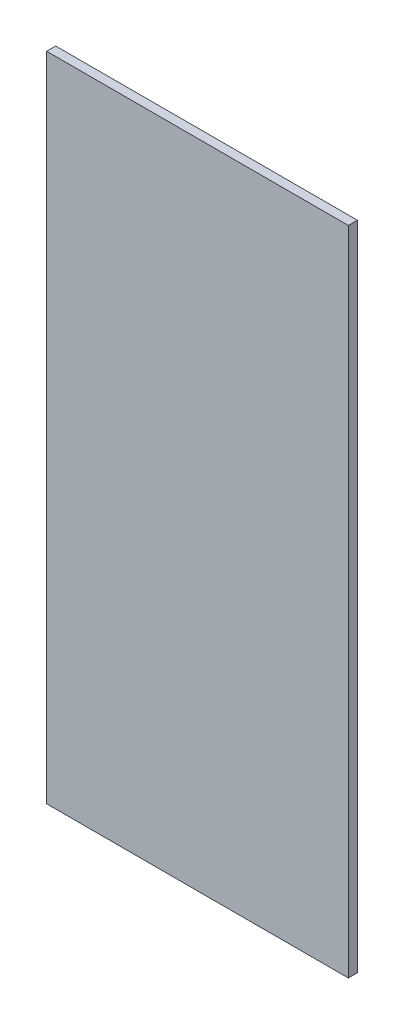
SolidWorks part; units mm, degrees
material "Pine"
ref_plane "Front Plane" through (0, 0, 0) normal (0, 0, 1) x (1, 0, 0)
ref_plane "Top Plane" through (0, 0, 0) normal (0, 1, 0) x (1, 0, 0)
ref_plane "Right Plane" through (0, 0, 0) normal (1, 0, 0) x (0, 0, -1)
sketch "Sketch1" plane through (0, 0, 0) normal (0, 0, 1) x (1, 0, 0)
  line L1 (0, 0) -> (635, 0)
  line L2 (0, 0) -> (0, -1371.6)
  line L3 (0, -1371.6) -> (635, -1371.6)
  line L4 (635, 0) -> (635, -1371.6)
  dimension "D1" = 635
  dimension "D2" = 1371.6
extrude "Boss-Extrude1" add sketch "Sketch1" along normal blind 19.05
equation "\"TableFrontWidth\"=64"
equation "\"TableSideWidth\"=28"
equation "\"LegWidth\"=3.5"
equation "\"LegHeight\"=32"
equation "\"LegDistToBottomStretcher\"=7"
equation "\"BottomStretcherLength\"=\"TableFrontWidth\""
equation "\"SideStretcherLength\"=\"TableSideWidth\"-3"
equation "\"BottomSupportLength\"=\"TableSideWidth\"-3"
equation "\"BottomPlywoodFrontDim\"=\"TableFrontWidth\"-\"LegWidth\"*2-3"
equation "\"BottomPlywoodSideDim\"=\"BottomSupportLength\""
equation "\"D2@Sketch1\"=\"BottomPlywoodFrontDim\""
equation "\"D1@Sketch1\"=\"BottomPlywoodSideDim\""
equation "\"TotalBottomSupports\"=4"
equation "\"TotalBottomSupportsLessOne\"=\"TotalBottomSupports\"-1"
equation "\"TotalTopSupports\"=5"
equation "\"TotalTopSupportsLessOne\"=\"TotalTopSupports\"-1"
equation "\"TopSupportSpread\"=\"TableFrontWidth\"-1.5"
equation "\"DistBetweenTopSupports\"=\"TopSupportSpread\"/\"TotalTopSupportsLessOne\""
equation "\"BottomSupportSpread\"= \"BottomPlywoodFrontDim\" - 1.5"
equation "\"DistBetweenBottomSupports\"=\"BottomSupportSpread\"/\"TotalBottomSupportsLessOne\""
equation "\"OverhangFrontDim\"=4"
equation "\"OverhangSideDim\"=4"
